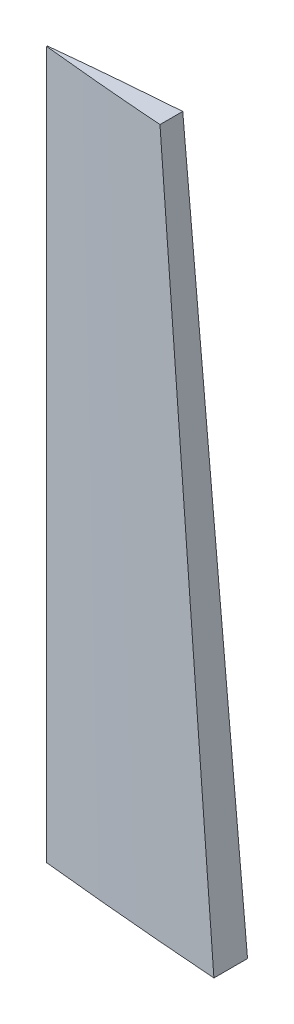
SolidWorks part; units mm, degrees
ref_plane "Front Plane" through (0, 0, 0) normal (0, 0, 1) x (1, 0, 0)
ref_plane "Top Plane" through (0, 0, 0) normal (0, 1, 0) x (1, 0, 0)
ref_plane "Right Plane" through (0, 0, 0) normal (1, 0, 0) x (0, 0, -1)
ref_plane "Plane1" through (0, 22, 0) normal (0, 1, 0) x (1, 0, 0)
sketch "Sketch1" plane through (0, 22, 0) normal (0, 1, 0) x (1, 0, 0)
  line L0 (-110.7624, 4.1051) -> (-110.7624, -4.1051)
  line L1 (-155.592, 0.1412) -> (-155.592, -0.1412)
  spline S0 degree 3 poles (-110.7624, 4.1051) (-110.9302, 4.0932) (-113.4216, 3.9174) (-118.0986, 3.5552) (-124.6337, 3.0335) (-130.6891, 2.5212) (-136.1989, 2.0342) (-141.1025, 1.5826) (-145.3462, 1.1776) (-148.8836, 0.8295) (-151.6759, 0.5476) (-153.6925, 0.3399) (-154.9114, 0.2128) (-155.4556, 0.1556) (-155.592, 0.1412) knots 0 0 0 0 0.011212 0.166483 0.312686 0.448211 0.571563 0.681381 0.776452 0.855723 0.918312 0.963525 0.990856 1 1 1 1
  spline S1 degree 3 poles (-110.7624, -4.1051) (-110.9302, -4.0932) (-113.4216, -3.9174) (-118.0986, -3.5552) (-124.6337, -3.0335) (-130.6891, -2.5212) (-136.1989, -2.0342) (-141.1025, -1.5826) (-145.3462, -1.1776) (-148.8836, -0.8295) (-151.6759, -0.5476) (-153.6925, -0.3399) (-154.9114, -0.2128) (-155.4556, -0.1556) (-155.592, -0.1412) knots 0 0 0 0 0.011212 0.166483 0.312686 0.448211 0.571563 0.681381 0.776452 0.855723 0.918312 0.963525 0.990856 1 1 1 1
ref_plane "Plane2" through (0, 194.49, 0) normal (0, 1, 0) x (1, 0, 0)
sketch "Sketch2" plane through (0, 194.49, 0) normal (0, 1, 0) x (1, 0, 0)
  line L0 (-125.2516, 2.7783) -> (-125.2516, -2.7783)
  line L1 (-155.592, 0.0956) -> (-155.592, -0.0956)
  spline S0 degree 3 poles (-125.2516, 2.7783) (-125.3651, 2.7703) (-127.0513, 2.6513) (-130.2167, 2.4062) (-134.6396, 2.053) (-138.7379, 1.7063) (-142.4668, 1.3767) (-145.7856, 1.0711) (-148.6577, 0.797) (-151.0518, 0.5614) (-152.9416, 0.3706) (-154.3064, 0.2301) (-155.1313, 0.144) (-155.4997, 0.1053) (-155.592, 0.0956) knots 0 0 0 0 0.011212 0.166483 0.312686 0.448211 0.571563 0.681381 0.776452 0.855723 0.918312 0.963525 0.990856 1 1 1 1
  spline S1 degree 3 poles (-125.2516, -2.7783) (-125.3651, -2.7703) (-127.0513, -2.6513) (-130.2167, -2.4062) (-134.6396, -2.053) (-138.7379, -1.7063) (-142.4668, -1.3767) (-145.7856, -1.0711) (-148.6577, -0.797) (-151.0518, -0.5614) (-152.9416, -0.3706) (-154.3064, -0.2301) (-155.1313, -0.144) (-155.4997, -0.1053) (-155.592, -0.0956) knots 0 0 0 0 0.011212 0.166483 0.312686 0.448211 0.571563 0.681381 0.776452 0.855723 0.918312 0.963525 0.990856 1 1 1 1
loft "Loft1" add profiles "Sketch1", "Sketch2"
